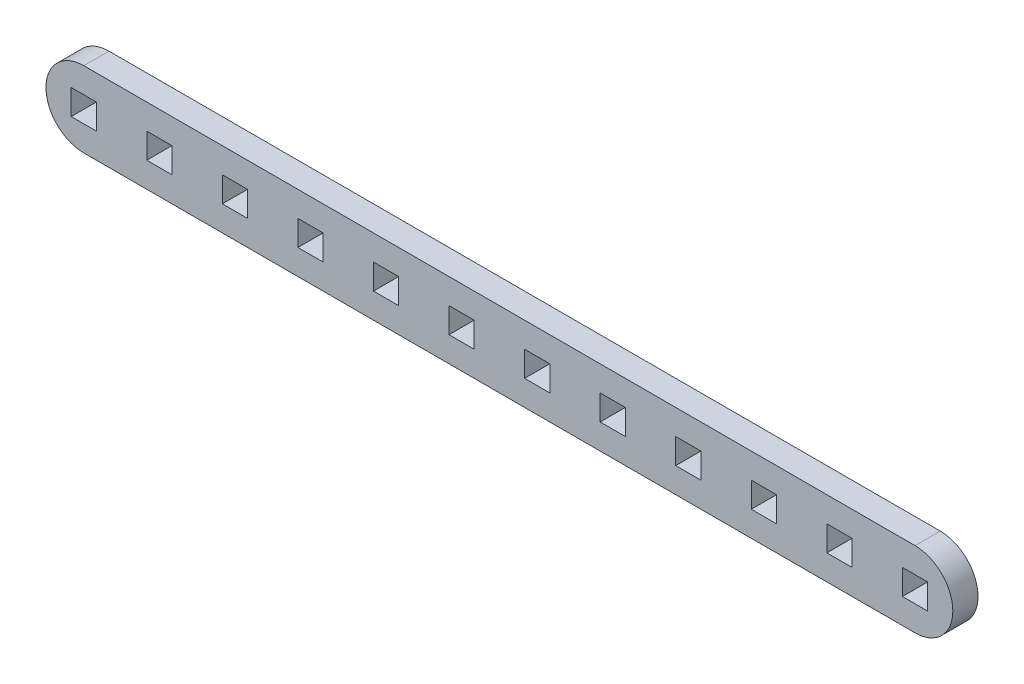
SolidWorks part; units mm, degrees
ref_plane "Alzado" through (0, 0, 0) normal (0, 0, 1) x (1, 0, 0)
ref_plane "Planta" through (0, 0, 0) normal (0, 1, 0) x (1, 0, 0)
ref_plane "Vista lateral" through (0, 0, 0) normal (1, 0, 0) x (0, 0, -1)
sketch "Model" plane through (0, 0, 0) normal (0, 0, 1) x (1, 0, 0)
  line L0 (8.4048, 293.775) -> (8.4048, 290.775)
  line L1 (11.4048, 293.775) -> (8.4048, 293.775)
  line L2 (11.4048, 290.775) -> (11.4048, 293.775)
  line L3 (8.4048, 290.775) -> (11.4048, 290.775)
  line L4 (17.4048, 293.775) -> (17.4048, 290.775)
  line L5 (20.4048, 293.775) -> (17.4048, 293.775)
  line L6 (20.4048, 290.775) -> (20.4048, 293.775)
  line L7 (17.4048, 290.775) -> (20.4048, 290.775)
  line L8 (26.4048, 293.775) -> (26.4048, 290.775)
  line L9 (29.4048, 293.775) -> (26.4048, 293.775)
  line L10 (29.4048, 290.775) -> (29.4048, 293.775)
  line L11 (26.4048, 290.775) -> (29.4048, 290.775)
  line L12 (35.4048, 293.775) -> (35.4048, 290.775)
  line L13 (38.4048, 293.775) -> (35.4048, 293.775)
  line L14 (38.4048, 290.775) -> (38.4048, 293.775)
  line L15 (35.4048, 290.775) -> (38.4048, 290.775)
  line L16 (44.4048, 293.775) -> (44.4048, 290.775)
  line L17 (47.4048, 293.775) -> (44.4048, 293.775)
  line L18 (47.4048, 290.775) -> (47.4048, 293.775)
  line L19 (44.4048, 290.775) -> (47.4048, 290.775)
  line L20 (53.4048, 293.775) -> (53.4048, 290.775)
  line L21 (56.4048, 293.775) -> (53.4048, 293.775)
  line L22 (56.4048, 290.775) -> (56.4048, 293.775)
  line L23 (53.4048, 290.775) -> (56.4048, 290.775)
  line L24 (62.4048, 293.775) -> (62.4048, 290.775)
  line L25 (65.4048, 293.775) -> (62.4048, 293.775)
  line L26 (65.4048, 290.775) -> (65.4048, 293.775)
  line L27 (62.4048, 290.775) -> (65.4048, 290.775)
  line L28 (71.4048, 293.775) -> (71.4048, 290.775)
  line L29 (74.4048, 293.775) -> (71.4048, 293.775)
  line L30 (74.4048, 290.775) -> (74.4048, 293.775)
  line L31 (71.4048, 290.775) -> (74.4048, 290.775)
  line L32 (80.4048, 293.775) -> (80.4048, 290.775)
  line L33 (83.4048, 293.775) -> (80.4048, 293.775)
  line L34 (83.4048, 290.775) -> (83.4048, 293.775)
  line L35 (80.4048, 290.775) -> (83.4048, 290.775)
  line L36 (89.4048, 293.775) -> (89.4048, 290.775)
  line L37 (92.4048, 293.775) -> (89.4048, 293.775)
  line L38 (92.4048, 290.775) -> (92.4048, 293.775)
  line L39 (89.4048, 290.775) -> (92.4048, 290.775)
  line L40 (107.4048, 293.775) -> (107.4048, 290.775)
  line L41 (110.4048, 293.775) -> (107.4048, 293.775)
  line L42 (110.4048, 290.775) -> (110.4048, 293.775)
  line L43 (107.4048, 290.775) -> (110.4048, 290.775)
  line L44 (98.4048, 293.775) -> (98.4048, 290.775)
  line L45 (101.4048, 293.775) -> (98.4048, 293.775)
  line L46 (101.4048, 290.775) -> (101.4048, 293.775)
  line L47 (98.4048, 290.775) -> (101.4048, 290.775)
  line L48 (9.9048, 296.775) -> (108.9048, 296.775)
  line L49 (9.9048, 287.775) -> (108.9048, 287.775)
  arc A0 (9.9048, 296.775) -> (9.9048, 287.775) centre (9.9048, 292.275) ccw
  arc A1 (108.9048, 287.775) -> (108.9048, 296.775) centre (108.9048, 292.275) ccw
extrude "Saliente-Extruir1" add sketch "Model" along normal blind 3
